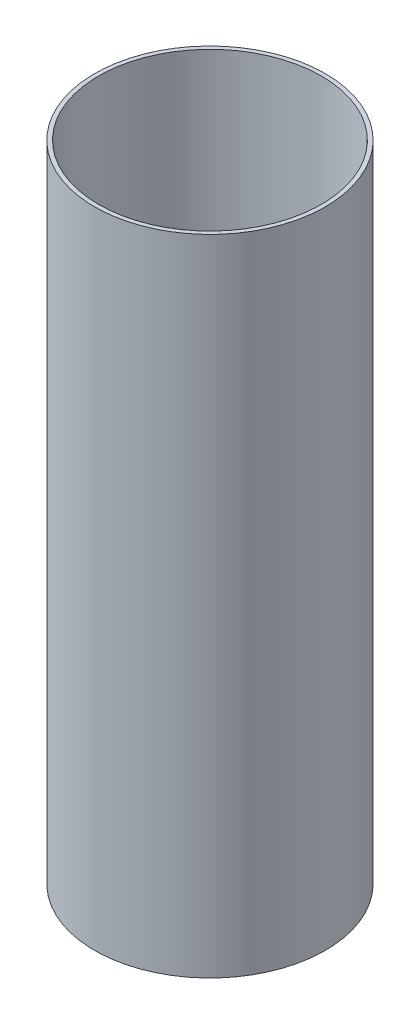
SolidWorks part; units mm, degrees
ref_plane "Front Plane" through (0, 0, 0) normal (0, 0, 1) x (1, 0, 0)
ref_plane "Top Plane" through (0, 0, 0) normal (0, 1, 0) x (1, 0, 0)
ref_plane "Right Plane" through (0, 0, 0) normal (1, 0, 0) x (0, 0, -1)
sketch "Sketch1" plane through (0, 0, 0) normal (0, 1, 0) x (1, 0, 0)
  circle A0 centre (0, 0) radius 26.35
  circle A1 centre (0, 0) radius 27.305
  dimension "D1" = 52.7
  dimension "D2" = 54.61
extrude "Boss-Extrude1" add sketch "Sketch1" along normal blind 152.4
